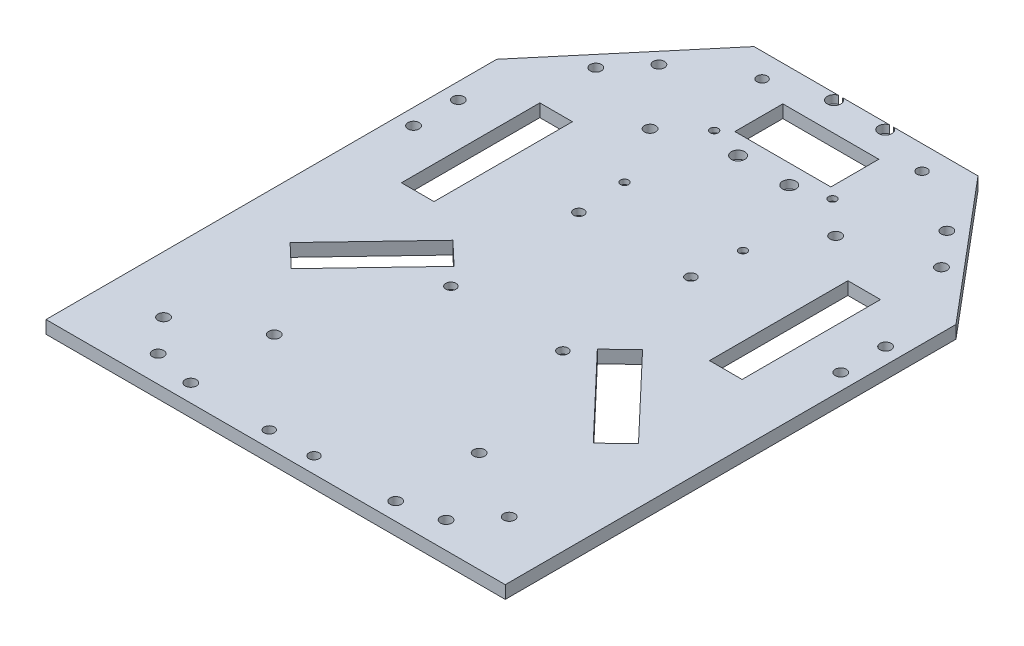
SolidWorks part; units mm, degrees
ref_plane "Front Plane" through (0, 0, 0) normal (0, 0, 1) x (1, 0, 0)
ref_plane "Top Plane" through (0, 0, 0) normal (0, 1, 0) x (1, 0, 0)
ref_plane "Right Plane" through (0, 0, 0) normal (1, 0, 0) x (0, 0, -1)
sketch "Sketch1" plane through (0, 0, 0) normal (0, 1, 0) x (1, 0, 0)
  line L1 (-35, -92.25) -> (35, -92.25)
  line L2 (-35, -92.25) -> (-35, 92.25)
  line L3 (-35, 92.25) -> (35, 92.25)
  line L4 (35, -92.25) -> (35, 92.25)
  line L5 (-35, -92.25) -> (35, 92.25) construction
  line L6 (-35, 92.25) -> (35, -92.25) construction
  point P0 (0, 0)
  dimension "D1" = 184.5
  dimension "D2" = 70
extrude "Boss-Extrude1" add sketch "Sketch1" along normal blind 4
sketch "Sketch2" plane through (0, 0, 0) normal (0, -1, 0) x (-1, 0, 0)
  line L0 (-35, 92.25) -> (35, 92.25) construction
  line L1 (35, 92.25) -> (35, -92.25) construction
  line L2 (-35, -92.25) -> (-35, 92.25) construction
  line L3 (0, 66.25) -> (0, 49.9252) construction
  line L4 (-15, 66.25) -> (15, 66.25)
  line L5 (-15, 66.25) -> (-15, 81.25)
  line L6 (-15, 81.25) -> (15, 81.25)
  line L7 (15, 66.25) -> (15, 81.25)
  line L8 (-15, 66.25) -> (15, 81.25) construction
  line L9 (-15, 81.25) -> (15, 66.25) construction
  circle A0 centre (25, 84.75) radius 1.6
  circle A1 centre (-25, 84.75) radius 1.6
  circle A2 centre (-8, 90.25) radius 1.1
  circle A3 centre (8, 90.25) radius 1.1
  circle A4 centre (-8, 60.25) radius 1.1
  circle A5 centre (8, 60.25) radius 1.1
  circle A6 centre (29, 53.75) radius 1.75
  circle A7 centre (-29, 53.75) radius 1.75
  point P25 (0, 73.75)
  dimension "D1" = 7.5
  dimension "D2" = 7.5
  dimension "D3" = 10
  dimension "D4" = 10
  dimension "D5" = 3.2
  dimension "D6" = 3.2
  dimension "D7" = 2.2
  dimension "D8" = 2.2
  dimension "D9" = 2.2
  dimension "D10" = 2.2
  dimension "D12" = 16
  dimension "D14" = 27
  dimension "D20" = 38.5
  dimension "D21" = 6
  dimension "D22" = 3.5
  dimension "D11" = 27
  dimension "D13" = 30
  dimension "D15" = 2
  dimension "D16" = 11
  dimension "D17" = 20
  dimension "D18" = 18.5
  dimension "D19" = 35
extrude "Cut-Extrude1" cut sketch "Sketch2" against normal blind 10
sketch "Sketch3" plane through (0, 4, 0) normal (0, 1, 0) x (1, 0, 0)
  line L0 (35, -92.25) -> (35, 92.25) construction
  line L1 (-71.775, 48.5927) -> (71.775, 48.5927)
  line L2 (-71.775, 48.5927) -> (-71.775, -92.288)
  line L3 (-71.775, -92.288) -> (71.775, -92.288)
  line L4 (71.775, 48.5927) -> (71.775, -92.288)
  line L5 (-71.775, 48.5927) -> (71.775, -92.288) construction
  line L6 (-71.775, -92.288) -> (71.775, 48.5927) construction
  line L7 (-35, 92.25) -> (-35, -92.25) construction
  point P0 (0, -21.8477)
  dimension "D1" = 35
  dimension "D2" = 35
extrude "Boss-Extrude2" add sketch "Sketch3" against normal blind 4
sketch "Sketch4" plane through (0, 4, 0) normal (0, 1, 0) x (1, 0, 0)
  line L0 (-35, 92.25) -> (-71.775, 48.5927)
  line L1 (-71.775, 48.5927) -> (-35, 48.5927)
  line L2 (-35, 48.5927) -> (-35, 92.25)
  line L3 (0, 92.25) -> (0, 52.9941) construction
  line L4 (35, 92.25) -> (-35, 92.25) construction
  line L5 (71.775, 48.5927) -> (35, 48.5927)
  line L6 (35, 92.25) -> (71.775, 48.5927)
  line L7 (35, 48.5927) -> (35, 92.25)
  line L8 (53.3875, 70.4214) -> (47.6983, 65.629) construction
  circle A0 centre (45, 72.5086) radius 1.75
  circle A1 centre (54.0195, 61.8012) radius 1.75
  circle A2 centre (-45, 72.5086) radius 1.75
  circle A3 centre (-54.0195, 61.8012) radius 1.75
  dimension "D1" = 3.5
  dimension "D2" = 10
  dimension "D3" = 7
extrude "Boss-Extrude3" add sketch "Sketch4" against normal blind 4
sketch "Sketch5" plane through (0, 4, 0) normal (0, 1, 0) x (1, 0, 0)
  line L0 (71.775, -92.288) -> (71.775, 48.5927) construction
  line L1 (-71.775, -92.288) -> (71.775, -92.288) construction
  line L2 (0, -92.288) -> (0, -87.9535) construction
  circle A0 centre (32.025, -86.788) radius 1.75
  circle A1 centre (-32.025, -86.788) radius 1.75
  dimension "D2" = 3.5
  dimension "D1" = 39.75
  dimension "D3" = 5.5
extrude "Cut-Extrude2" cut sketch "Sketch5" against normal blind 6
sketch "Sketch7" plane through (0, 4, 0) normal (0, 1, 0) x (1, 0, 0)
  line L8 (-29.6387, -7.236) -> (-22.393, -14.1279)
  line L9 (-22.393, -14.1279) -> (-47.204, -40.2126)
  line L10 (-47.204, -40.2126) -> (-54.4497, -33.3207)
  line L11 (-54.4497, -33.3207) -> (-29.6387, -7.236)
  line L12 (35, 92.25) -> (-35, 92.25) construction
  line L13 (0, 92.25) -> (0, 70.9075) construction
  line L14 (54.4497, -33.3207) -> (29.6387, -7.236)
  line L15 (47.204, -40.2126) -> (54.4497, -33.3207)
  line L16 (22.393, -14.1279) -> (47.204, -40.2126)
  line L17 (29.6387, -7.236) -> (22.393, -14.1279)
  point P8 (0, 92.25)
  dimension "D2" = 10
extrude "Cut-Extrude4" cut sketch "Sketch7" against normal up to next
sketch "Sketch8" plane through (0, 4, 0) normal (0, 1, 0) x (1, 0, 0)
  circle A0 centre (-8, 90.25) radius 2.1
  circle A1 centre (8, 90.25) radius 2.1
  circle A2 centre (-8, 60.25) radius 2.1
  circle A3 centre (8, 60.25) radius 2.1
  dimension "D1" = 4.2
extrude "Cut-Extrude7" cut sketch "Sketch8" against normal blind 2.5
sketch "Sketch9" plane through (0, 4, 0) normal (0, 1, 0) x (1, 0, 0)
  line L0 (0, 0) -> (0, -35.5885) construction
  circle A0 centre (-32.025, -60.698) radius 1.75
  circle A2 centre (-32.025, -86.788) radius 1.75 construction
  circle A3 centre (32.025, -60.698) radius 1.75
  dimension "D1" = 3.5
  dimension "D2" = 26.09
extrude "Cut-Extrude8" cut sketch "Sketch9" against normal blind 12
sketch "Sketch10" plane through (0, 4, 0) normal (0, 1, 0) x (1, 0, 0)
  line L0 (-71.775, 48.5927) -> (-71.775, -92.288) construction
  line L1 (-71.775, -5.75) -> (88.0218, -5.75) construction
  line L2 (35, 92.25) -> (8.6403, 92.25) construction
  line L3 (0, 92.25) -> (0, 26.3925) construction
  line L4 (7.3597, 92.25) -> (-7.3597, 92.25) construction
  line L5 (53.2384, 43.5297) -> (43.0457, 43.5297)
  line L6 (-53.2384, 0.2725) -> (-43.0457, 0.2725)
  line L7 (-53.2384, 0.2725) -> (-53.2384, 43.5297)
  line L8 (-53.2384, 43.5297) -> (-43.0457, 43.5297)
  line L9 (-43.0457, 0.2725) -> (-43.0457, 43.5297)
  line L10 (-53.2384, 0.2725) -> (-43.0457, 43.5297) construction
  line L11 (-53.2384, 43.5297) -> (-43.0457, 0.2725) construction
  line L12 (43.0457, 0.2725) -> (43.0457, 43.5297)
  line L13 (53.2384, 0.2725) -> (43.0457, 0.2725)
  line L14 (53.2384, 0.2725) -> (53.2384, 43.5297)
  circle A0 centre (-66.775, 31.5927) radius 1.75
  circle A1 centre (-66.775, 17.5927) radius 1.75
  circle A2 centre (66.775, 31.5927) radius 1.75
  circle A3 centre (66.775, 17.5927) radius 1.75
  circle A4 centre (-54.0195, 61.8012) radius 1.75
  circle A5 centre (-45, 72.5086) radius 1.75
  circle A6 centre (45, 72.5086) radius 1.75
  circle A7 centre (54.0195, 61.8012) radius 1.75
  circle A8 centre (54.0195, -73.3012) radius 1.75
  circle A9 centre (45, -84.0086) radius 1.75
  circle A10 centre (-45, -84.0086) radius 1.75
  circle A11 centre (-54.0195, -73.3012) radius 1.75
  point P40 (-48.142, 21.9011)
  dimension "D2" = 3.5
  dimension "D4" = 3.5
  dimension "D1" = 5
  dimension "D3" = 14
  dimension "D5" = 17
  dimension "D6" = 98
extrude "Cut-Extrude9" cut sketch "Sketch10" against normal blind 10
sketch "Sketch11" plane through (0, 4, 0) normal (0, 1, 0) x (1, 0, 0)
  line L5 (-17.5, -20) -> (17.5, 20) construction
  line L6 (-17.5, 20) -> (17.5, -20) construction
  circle A0 centre (-17.5, 20) radius 1.6
  circle A1 centre (17.5, 20) radius 1.6
  circle A2 centre (-17.5, -20) radius 1.6
  circle A3 centre (17.5, -20) radius 1.6
  point P0 (0, 0)
  dimension "D3" = 3.2
  dimension "D4" = 3.2
  dimension "D5" = 3.2
  dimension "D6" = 3.2
  dimension "D1" = 35
  dimension "D2" = 40
extrude "Cut-Extrude10" cut sketch "Sketch11" against normal blind 10
sketch "Sketch12" plane through (0, 0, 0) normal (0, -1, 0) x (1, 0, 0)
  line L1 (-14.65, -21.6454) -> (-14.65, -18.3546)
  line L2 (-14.65, -18.3546) -> (-17.5, -16.7091)
  line L3 (-17.5, -16.7091) -> (-20.35, -18.3546)
  line L4 (-20.35, -18.3546) -> (-20.35, -21.6454)
  line L5 (-20.35, -21.6454) -> (-17.5, -23.2909)
  line L6 (-17.5, -23.2909) -> (-14.65, -21.6454)
  line L7 (17.5, -23.2909) -> (20.35, -21.6454)
  line L8 (20.35, -21.6454) -> (20.35, -18.3546)
  line L9 (20.35, -18.3546) -> (17.5, -16.7091)
  line L10 (17.5, -16.7091) -> (14.65, -18.3546)
  line L11 (14.65, -18.3546) -> (14.65, -21.6454)
  line L12 (14.65, -21.6454) -> (17.5, -23.2909)
  line L13 (-17.5, 16.7091) -> (-14.65, 18.3546)
  line L14 (-14.65, 18.3546) -> (-14.65, 21.6454)
  line L15 (-14.65, 21.6454) -> (-17.5, 23.2909)
  line L16 (-17.5, 23.2909) -> (-20.35, 21.6454)
  line L17 (-20.35, 21.6454) -> (-20.35, 18.3546)
  line L18 (-20.35, 18.3546) -> (-17.5, 16.7091)
  line L19 (17.5, 23.2909) -> (14.65, 21.6454)
  line L20 (14.65, 21.6454) -> (14.65, 18.3546)
  line L21 (14.65, 18.3546) -> (17.5, 16.7091)
  line L22 (17.5, 16.7091) -> (20.35, 18.3546)
  line L23 (20.35, 18.3546) -> (20.35, 21.6454)
  line L24 (20.35, 21.6454) -> (17.5, 23.2909)
  circle A0 centre (-17.5, -20) radius 2.85 construction
  circle A1 centre (17.5, -20) radius 2.85 construction
  circle A2 centre (-17.5, 20) radius 2.85 construction
  circle A3 centre (17.5, 20) radius 2.85 construction
  dimension "D1" = 5.7
  dimension "D2" = 5.7
  dimension "D3" = 5.7
  dimension "D4" = 5.7
extrude "Cut-Extrude11" cut sketch "Sketch12" against normal blind 2
sketch "Sketch13" plane through (0, 4, 0) normal (0, 1, 0) x (1, 0, 0)
  line L0 (7.3597, 92.25) -> (-7.3597, 92.25) construction
  line L1 (-18.5, 63.2726) -> (18.5, 63.2726)
  line L2 (-18.5, 63.2726) -> (-18.5, 35.2726)
  line L3 (-18.5, 35.2726) -> (18.5, 35.2726)
  line L4 (18.5, 63.2726) -> (18.5, 35.2726)
  line L5 (-18.5, 63.2726) -> (18.5, 35.2726) construction
  line L6 (-18.5, 35.2726) -> (18.5, 63.2726) construction
  circle A0 centre (-18.5, 63.2726) radius 1.25
  circle A1 centre (18.5, 63.2726) radius 1.25
  circle A2 centre (-18.5, 35.2726) radius 1.25
  circle A3 centre (18.5, 35.2726) radius 1.25
  point P0 (0, 49.2726)
  point P9 (0, 92.25)
  dimension "D3" = 2.5
  dimension "D4" = 2.5
  dimension "D5" = 2.5
  dimension "D6" = 2.5
  dimension "D1" = 37
  dimension "D2" = 28
extrude "Cut-Extrude12" cut sketch "Sketch13" against normal blind 12 contours L2 A2 L3 | L3 A2 L2 | L3 A3 L4 | L4 A3 L3 | L4 A1 L1 | L1 A1 L4 | L1 A0 L2 | L2 A0 L1
sketch "Sketch14" plane through (0, 4, 0) normal (0, 1, 0) x (1, 0, 0)
  line L0 (0, -92.288) -> (0, -75.1332) construction
  line L1 (-71.775, -92.288) -> (71.775, -92.288) construction
  circle A0 centre (-7, -87.288) radius 1.6
  circle A1 centre (7, -87.288) radius 1.6
  dimension "D1" = 3.2
  dimension "D2" = 7
  dimension "D3" = 5
extrude "Cut-Extrude13" cut sketch "Sketch14" against normal blind 12
sketch "Sketch15" plane through (0, 0, 0) normal (0, -1, 0) x (1, 0, 0)
  circle A0 centre (-18.5, -35.2726) radius 2.5
  circle A1 centre (18.5, -35.2726) radius 2.5
  circle A2 centre (-18.5, -63.2726) radius 2.5
  circle A3 centre (18.5, -63.2726) radius 2.5
  dimension "D1" = 5
  dimension "D2" = 5
  dimension "D3" = 5
  dimension "D4" = 5
extrude "Cut-Extrude14" cut sketch "Sketch15" against normal blind 2.5
